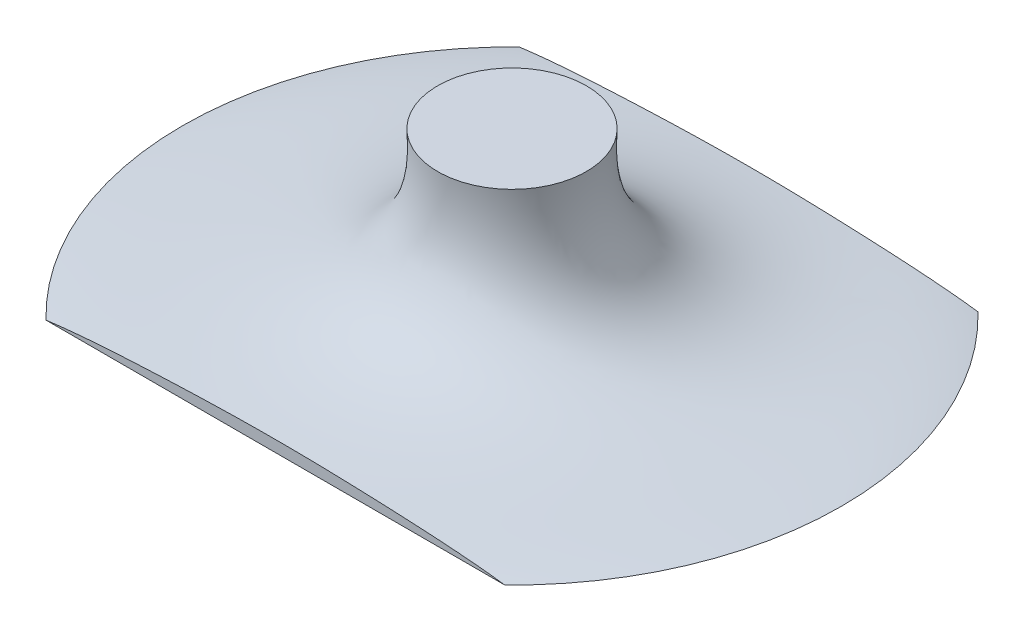
SolidWorks part; units mm, degrees
ref_plane "Front Plane" through (0, 0, 0) normal (0, 0, 1) x (1, 0, 0)
ref_plane "Top Plane" through (0, 0, 0) normal (0, 1, 0) x (1, 0, 0)
ref_plane "Right Plane" through (0, 0, 0) normal (1, 0, 0) x (0, 0, -1)
sketch "Sketch2" plane through (0, 0, 0) normal (0, 0, 1) x (1, 0, 0)
  line L0 (0, -24) -> (97.5, -24)
  line L1 (0, -24) -> (0, 24)
  line L2 (0, 24) -> (22, 24)
  spline S0 degree 3 poles (97.5, -24) (66.7019, -17.9991) (18.637, -25.1736) (22, 24) knots 0 0 0 0 1 1 1 1
  point P2 (-138.644, 125.3396)
  point P5 (0, 0)
  point P7 (0, 0)
  point P9 (0, 0)
  point P10 (-96.7687, 115.6012)
  point P11 (0, 0)
  point P12 (0, 0)
  dimension "D1" = 97.5
  dimension "D2" = 48
  dimension "D3" = 22
  dimension "D4" = 12.1449
  dimension "D5" = 2.4065
  dimension "D6" = 18.3177
  dimension "D7" = 41.8752
revolve "Revolve1" add sketch "Sketch2" angle 360 about L1
sketch "Sketch3" plane through (0, 24, 0) normal (0, 1, 0) x (1, 0, 0)
  line L1 (-125, 70) -> (125, 70)
  line L2 (-125, 70) -> (-125, -70)
  line L3 (-125, -70) -> (125, -70)
  line L4 (125, 70) -> (125, -70)
  line L5 (-125, 70) -> (125, 70)
  line L6 (-125, 70) -> (-125, 106)
  line L7 (-125, 106) -> (125, 106)
  line L8 (125, 70) -> (125, 106)
  line L9 (-125, -70) -> (125, -70)
  line L10 (-125, -70) -> (-125, -106)
  line L11 (-125, -106) -> (125, -106)
  line L12 (125, -70) -> (125, -106)
  dimension "D1" = 140
  dimension "D2" = 70
  dimension "D3" = 250
  dimension "D4" = 125
  dimension "D5" = 36
  dimension "D6" = 36
extrude "Cut-Extrude1" cut sketch "Sketch3" against normal blind 100 and the other way through all contours L1 L8 L7 L6 | L12 L3 L10 L11
equation "\"D2@Sketch3\"=\"D1@Sketch3\"/2"
equation "\"D4@Sketch3\"=\"D3@Sketch3\"/2"
equation "\"D6@Sketch3\"=\"D5@Sketch3\""
